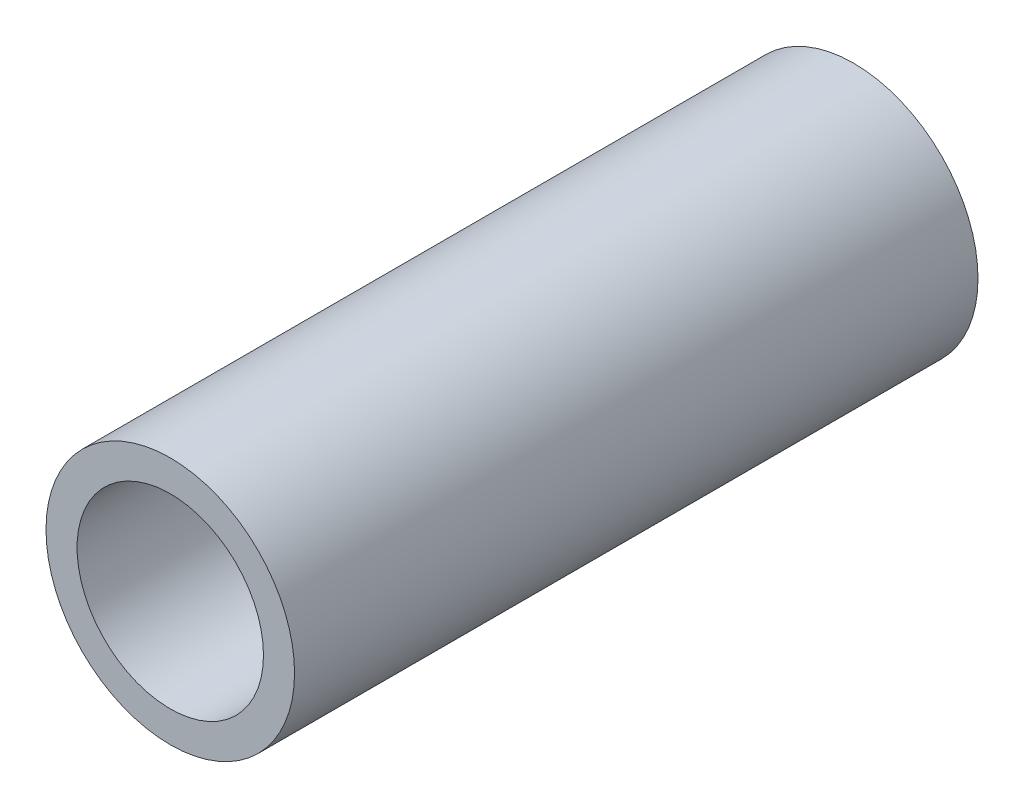
SolidWorks part; units mm, degrees
ref_plane "Front Plane" through (0, 0, 0) normal (0, 0, 1) x (1, 0, 0)
ref_plane "Top Plane" through (0, 0, 0) normal (0, 1, 0) x (1, 0, 0)
ref_plane "Right Plane" through (0, 0, 0) normal (1, 0, 0) x (0, 0, -1)
sketch "Sketch1" plane through (0, 0, 0) normal (0, 0, 1) x (1, 0, 0)
  circle A0 centre (0, 0) radius 4
  dimension "D1" = 8
extrude "Extrude-Thin1" add sketch "Sketch1" along normal blind 22 thin thin type one direction reverse wall 1
